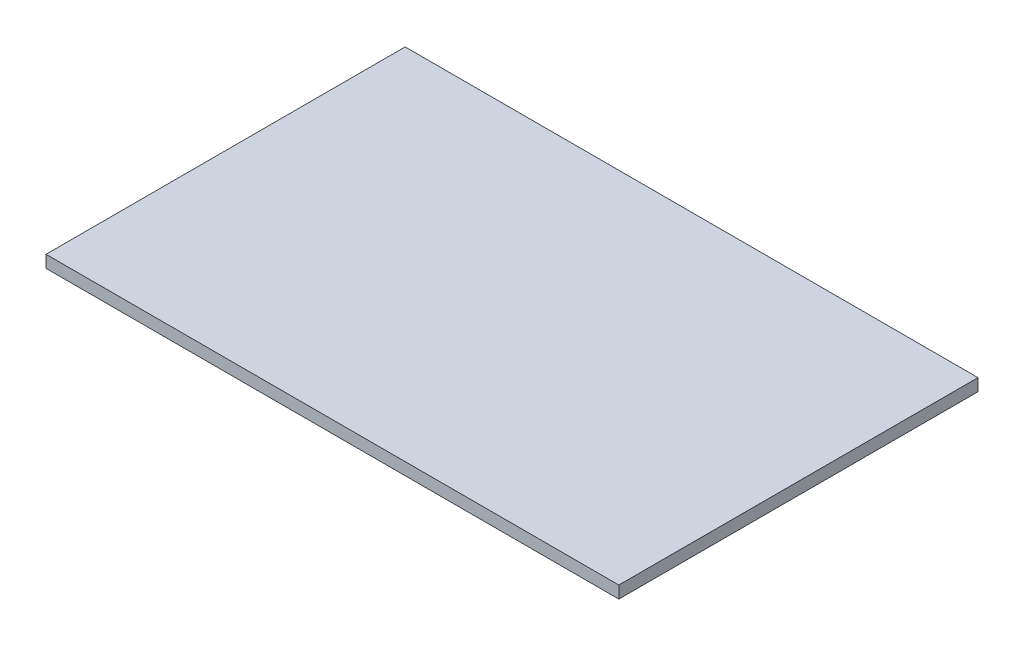
SolidWorks part; units mm, degrees
ref_plane "前视基准面" through (0, 0, 0) normal (0, 0, 1) x (1, 0, 0)
ref_plane "上视基准面" through (0, 0, 0) normal (0, 1, 0) x (1, 0, 0)
ref_plane "右视基准面" through (0, 0, 0) normal (1, 0, 0) x (0, 0, -1)
sketch "草图1" plane through (0, 0, 0) normal (0, 1, 0) x (1, 0, 0)
  line L1 (0, 0) -> (-56.3, 0)
  line L2 (0, 0) -> (0, 35.3)
  line L3 (0, 35.3) -> (-56.3, 35.3)
  line L4 (-56.3, 0) -> (-56.3, 35.3)
extrude "凸台-拉伸1" add sketch "草图1" along normal blind 1.2
